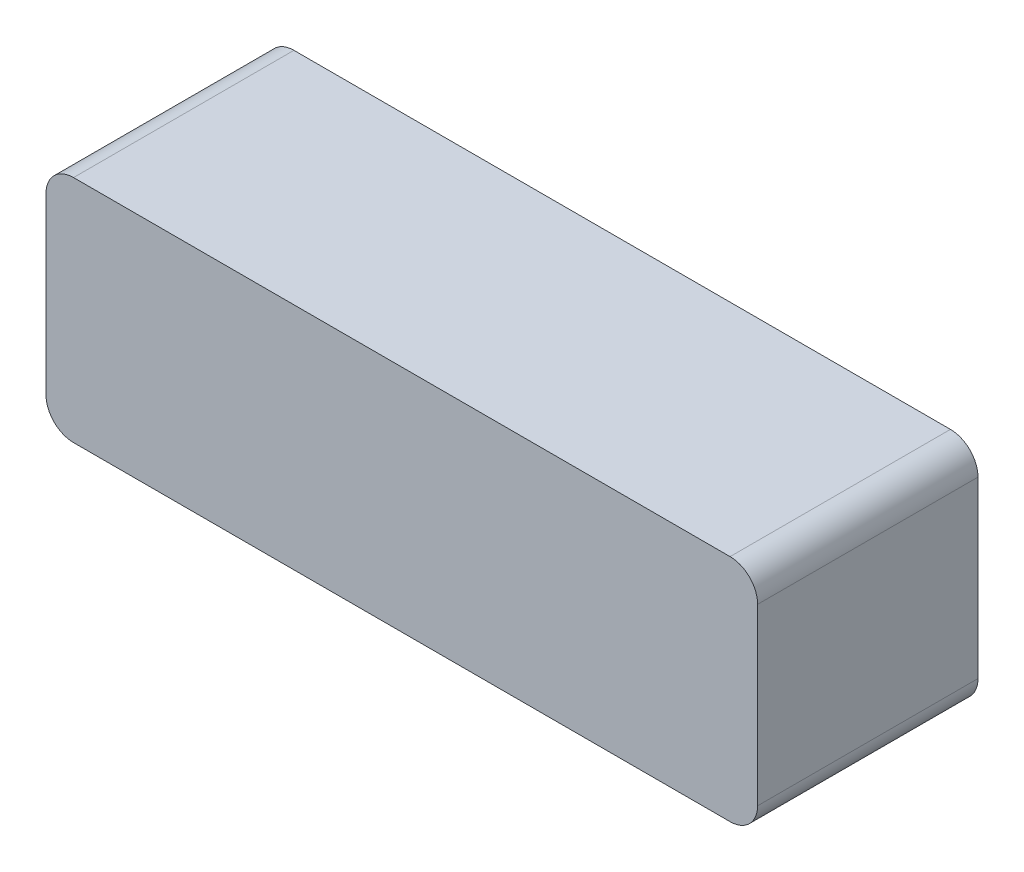
SolidWorks part; units mm, degrees
ref_plane "Front Plane" through (0, 0, 0) normal (0, 0, 1) x (1, 0, 0)
ref_plane "Top Plane" through (0, 0, 0) normal (0, 1, 0) x (1, 0, 0)
ref_plane "Right Plane" through (0, 0, 0) normal (1, 0, 0) x (0, 0, -1)
sketch "Sketch1" plane through (0, 0, 0) normal (0, 0, 1) x (1, 0, 0)
  line L0 (-71.5, -25) -> (71.5, -25)
  line L1 (77.5, -19) -> (77.5, 19)
  line L2 (71.5, 25) -> (-71.5, 25)
  line L3 (-77.5, 19) -> (-77.5, -19)
  arc A0 (71.5, -25) -> (77.5, -19) centre (71.5, -19) ccw
  arc A1 (77.5, 19) -> (71.5, 25) centre (71.5, 19) ccw
  arc A2 (-71.5, 25) -> (-77.5, 19) centre (-71.5, 19) ccw
  arc A3 (-77.5, -19) -> (-71.5, -25) centre (-71.5, -19) ccw
extrude "Boss-Extrude1" add sketch "Sketch1" along normal mid plane 48
